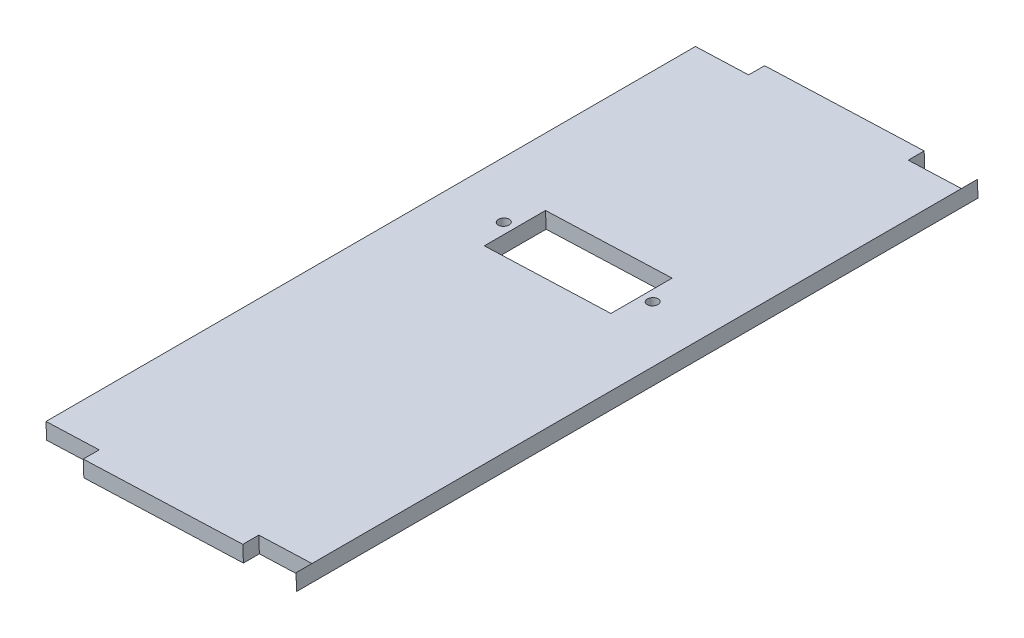
SolidWorks part; units mm, degrees
material "轻木"
ref_plane "前视基准面" through (0, 0, 0) normal (0, 0, 1) x (1, 0, 0)
ref_plane "上视基准面" through (0, 0, 0) normal (0, 1, 0) x (1, 0, 0)
ref_plane "右视基准面" through (0, 0, 0) normal (1, 0, 0) x (0, 0, -1)
other "Configuration Table"
sketch "草图2" plane through (0, 0, 762.01) normal (0, 0, -1) x (-1, 0, 0)
  line L0 (-11.3772, -6.0133) -> (-11.4961, -9.0107) construction
  line L1 (-21.3703, -5.6399) -> (28.5949, -7.5069)
  line L2 (-21.3703, -5.6399) -> (-21.4892, -8.6375)
  line L3 (-21.4892, -8.6375) -> (28.476, -10.5046)
  line L4 (28.5949, -7.5069) -> (28.476, -10.5046)
  spline S0 degree 3 poles (1123.171, 1542.7978) (737.8393, -23.0908) (370.6443, -24.5252) (-354.1685, 4.9567) (-721.2535, -15.5864) (-1004.8758, -1634.9014) knots -1.057605 -1.057605 -1.057605 -1.057605 0.710947 0.741076 2.483068 2.483068 2.483068 2.483068 only from (18.4806, -10.1929) to (-11.4961, -9.0107) construction
  spline S1 degree 3 poles (1161.3711, 1554.4711) (623.0613, -51.2946) (315.6776, -18.8655) (-371.5594, 8.1594) (-752.3268, -11.6385) (-895.779, -1677.1566) knots -3.625683 -3.625683 -3.625683 -3.625683 0.625 0.625 5.577222 5.577222 5.577222 5.577222 only from (18.5995, -7.1948) to (-11.3772, -6.0133) construction
  spline S2 degree 3 poles (18.4806, -10.1929) (17.2439, -10.144) (9.8398, -9.8494) (-0.1514, -9.443) (-8.9084, -9.1075) (-11.4961, -9.0107) knots 0.704906 0.704906 0.704906 0.704906 0.710947 0.741076 0.753712 0.753712 0.753712 0.753712 construction
  spline S3 degree 3 poles (18.5995, -7.1948) (11.8204, -6.9259) (5.0391, -6.65) (-4.9562, -6.2569) (-8.1664, -6.1333) (-11.3772, -6.0133) knots 0.534129 0.534129 0.534129 0.534129 0.625 0.625 0.667977 0.667977 0.667977 0.667977 construction
  dimension "D1" = 3
  dimension "D2" = 50
  dimension "D3" = 10
extrude "凸台-拉伸1" add sketch "草图2" against normal blind 128
sketch "草图3" plane through (0.2402, -6.4295, 0) normal (-0.0373, 0.9993, 0) x (0.9993, 0.0373, 0)
  line L0 (-18.8552, -762.01) -> (-28.8553, -762.01)
  line L1 (21.1448, -762.01) -> (11.1447, -762.01)
  line L2 (21.1448, -762.01) -> (21.1448, -765.01)
  line L3 (21.1448, -765.01) -> (11.1447, -765.01)
  line L4 (11.1447, -762.01) -> (11.1447, -765.01)
  line L5 (-18.8552, -762.01) -> (-18.8552, -765.01)
  line L6 (-18.8552, -765.01) -> (-28.8553, -765.01)
  line L7 (-28.8553, -762.01) -> (-28.8553, -765.01)
  line L8 (-18.8552, -887.01) -> (-28.8553, -887.01)
  line L9 (-18.8552, -887.01) -> (-18.8552, -890.01)
  line L10 (-18.8552, -890.01) -> (-28.8553, -890.01)
  line L11 (-28.8553, -887.01) -> (-28.8553, -890.01)
  line L12 (21.1448, -887.01) -> (11.1447, -887.01)
  line L13 (21.1448, -887.01) -> (21.1448, -890.01)
  line L14 (21.1448, -890.01) -> (11.1447, -890.01)
  line L15 (11.1447, -887.01) -> (11.1447, -890.01)
  line L16 (21.1448, -762.01) -> (-18.8552, -762.01) construction
  line L17 (21.1448, -762.01) -> (21.1448, -887.01) construction
  dimension "D1" = 90
  dimension "D2" = 40
  dimension "D3" = 125
extrude "切除-拉伸1" cut sketch "草图3" against normal through all
sketch "草图4" plane through (0.2402, -6.4295, 0) normal (-0.0373, 0.9993, 0) x (0.9993, 0.0373, 0)
  line L0 (-18.8552, -762.01) -> (11.1447, -762.01) construction
  line L1 (-15.7552, -806.26) -> (8.0448, -806.26)
  line L2 (-15.7552, -806.26) -> (-15.7552, -817.76)
  line L3 (-15.7552, -817.76) -> (8.0448, -817.76)
  line L4 (8.0448, -806.26) -> (8.0448, -817.76)
  line L5 (-15.7552, -806.26) -> (8.0448, -817.76) construction
  line L6 (-15.7552, -817.76) -> (8.0448, -806.26) construction
  line L7 (-28.8552, -887.01) -> (-28.8552, -765.01) construction
  line L8 (-3.8552, -1825.01) -> (-3.8552, 48174.99) construction
  circle A0 centre (10.1448, -812.01) radius 1
  circle A1 centre (-17.8552, -812.01) radius 1
  point P0 (-3.8552, -812.01)
  dimension "D5" = 2
  dimension "D1" = 50
  dimension "D2" = 11.5
  dimension "D3" = 23.8
  dimension "D4" = 25
  dimension "D6" = 14
extrude "切除-拉伸2" cut sketch "草图4" against normal through all
